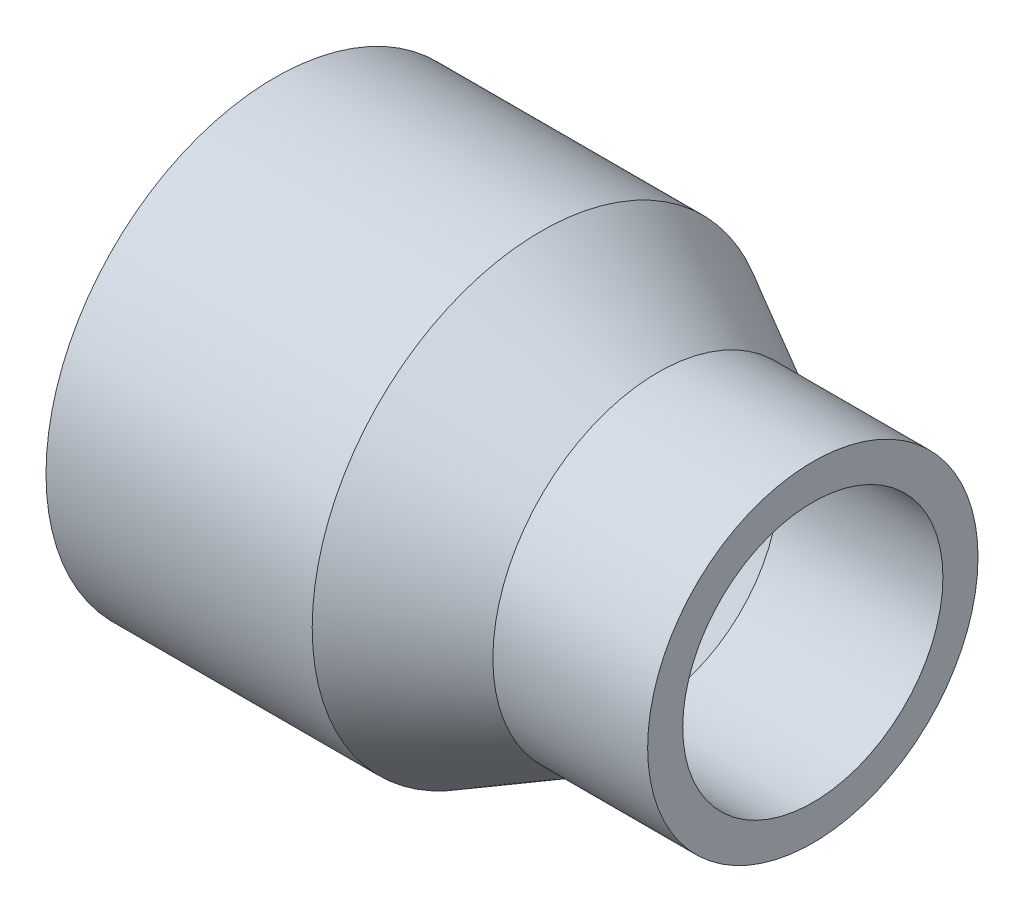
SolidWorks part; units mm, degrees
ref_plane "Front Plane" through (0, 0, 0) normal (0, 0, 1) x (1, 0, 0)
ref_plane "Top Plane" through (0, 0, 0) normal (0, 1, 0) x (1, 0, 0)
ref_plane "Right Plane" through (0, 0, 0) normal (1, 0, 0) x (0, 0, -1)
sketch "Sketch1" plane through (0, 0, 0) normal (0, 1, 0) x (1, 0, 0)
  line L0 (0, 16.575) -> (12, 16.575)
  line L1 (12, 16.575) -> (22, 11.125)
  line L2 (22, 11.125) -> (36, 11.125)
  line L3 (0, 0) -> (85.0578, 0) construction
  line L4 (0, 19.575) -> (12.7644, 19.575)
  line L5 (12.7644, 19.575) -> (22.7644, 14.125)
  line L6 (22.7644, 14.125) -> (36, 14.125)
  line L7 (0, 19.575) -> (0, 16.575)
  line L8 (36, 14.125) -> (36, 11.125)
  dimension "D1" = 12
  dimension "D2" = 16.575
  dimension "D3" = 11.125
  dimension "D4" = 14
  dimension "D5" = 10
  dimension "D6" = 3
revolve "Revolve1" add sketch "Sketch1" angle 360 about L3
sketch "Sketch2" plane through (0, 0, 0) normal (-1, 0, 0) x (0, 0, 1)
  circle A0 centre (0, 0) radius 17.1
  circle A1 centre (0, 0) radius 19.575
  dimension "D1" = 34.2
extrude "Boss-Extrude1" add sketch "Sketch2" along normal blind 10
